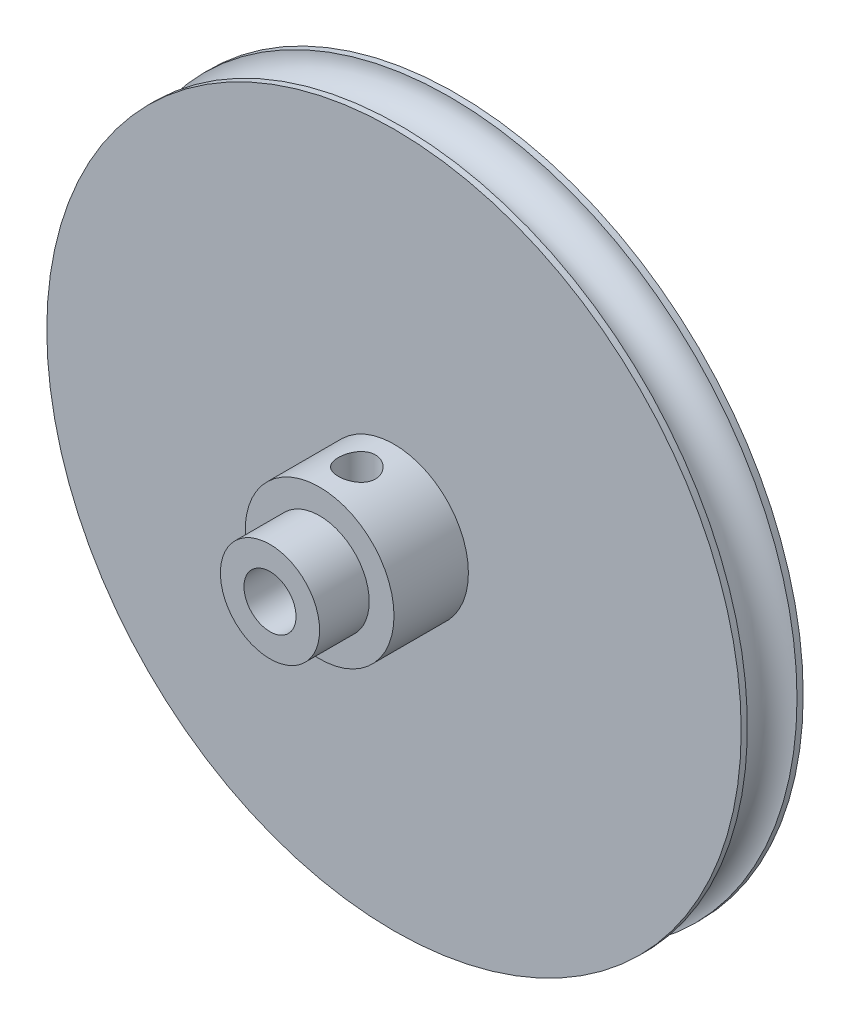
SolidWorks part; units mm, degrees
ref_plane "Plan de face" through (0, 0, 0) normal (0, 0, 1) x (1, 0, 0)
ref_plane "Plan de dessus" through (0, 0, 0) normal (0, 1, 0) x (1, 0, 0)
ref_plane "Plan de droite" through (0, 0, 0) normal (1, 0, 0) x (0, 0, -1)
sketch "Esquisse1" plane through (0, 0, 0) normal (0, 0, 1) x (1, 0, 0)
  circle A0 centre (0, 0) radius 28
  dimension "D1" = 56
extrude "Boss.-Extru.1" add sketch "Esquisse1" along normal blind 5
sketch "Esquisse2" plane through (0, 0, 5) normal (0, 0, 1) x (1, 0, 0)
  circle A0 centre (0, 0) radius 4
extrude "Boss.-Extru.2" add sketch "Esquisse2" along normal blind 10
sketch "Esquisse3" plane through (0, 0, 15) normal (0, 0, 1) x (1, 0, 0)
  circle A0 centre (0, 0) radius 2.1
  dimension "D1" = 4.2
extrude "Enlèv. mat.-Extru.1" cut sketch "Esquisse3" against normal through all
sketch "Esquisse4" plane through (0, 0, 0) normal (1, 0, 0) x (0, 0, -1)
  line L0 (-2.5, 28) -> (-2.5, 8.0945) construction
  line L1 (0, 28) -> (-5, 28) construction
  line L2 (0, 0) -> (-21.8888, 0) construction
  line L3 (-2.5, 0) -> (-2.5, -28) construction
  circle A1 centre (-2.5, 28) radius 2
  circle A2 centre (-2.5, -28) radius 2 construction
  dimension "D1" = 4
revolve "Enlèvement de matière-Révolution1" cut sketch "Esquisse4" angle 360 about L2
sketch "Esquisse5" plane through (0, 0, 5) normal (0, 0, 1) x (1, 0, 0)
  circle A0 centre (0, 0) radius 4
  circle A1 centre (0, 0) radius 6
extrude "Boss.-Extru.3" add sketch "Esquisse5" along normal blind 6
sketch "Esquisse6" plane through (0, 0, 0) normal (0, 1, 0) x (1, 0, 0)
  line L0 (0, -11) -> (0, -5) construction
  line L1 (-4, -11) -> (4, -11) construction
  line L2 (-6, -5) -> (6, -5) construction
  circle A0 centre (0, -8) radius 1.5
extrude "Enlèv. mat.-Extru.2" cut sketch "Esquisse6" along normal up to next
